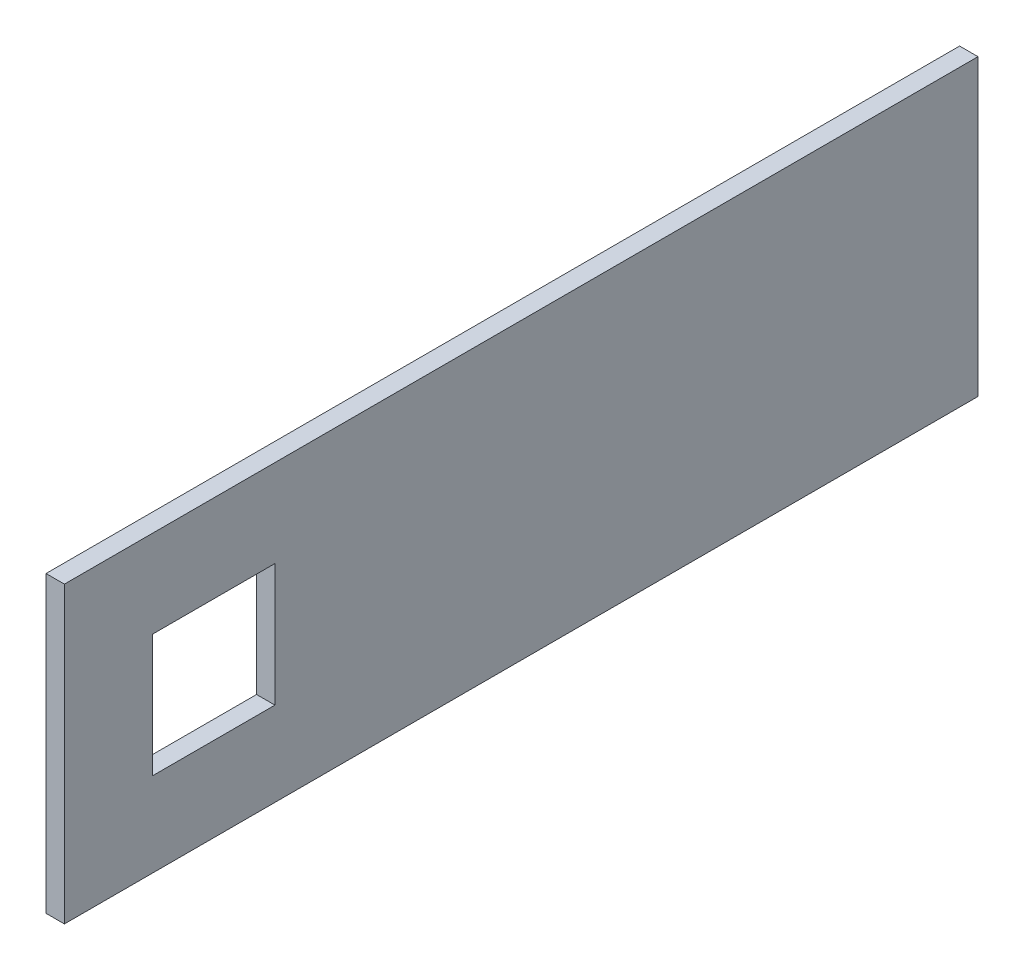
SolidWorks part; units mm, degrees
ref_plane "Front Plane" through (0, 0, 0) normal (0, 0, 1) x (1, 0, 0)
ref_plane "Top Plane" through (0, 0, 0) normal (0, 1, 0) x (1, 0, 0)
ref_plane "Right Plane" through (0, 0, 0) normal (1, 0, 0) x (0, 0, -1)
sketch "Sketch1" plane through (0, 0, 0) normal (1, 0, 0) x (0, 0, -1)
  line L1 (-74.5, 24) -> (74.5, 24)
  line L2 (-74.5, 24) -> (-74.5, -24)
  line L3 (-74.5, -24) -> (74.5, -24)
  line L4 (74.5, 24) -> (74.5, -24)
  line L5 (-74.5, 24) -> (74.5, -24) construction
  line L6 (-74.5, -24) -> (74.5, 24) construction
  line L7 (-60.1601, 9.7414) -> (-40.1601, 9.7414)
  line L8 (-60.1601, 9.7414) -> (-60.1601, -10.2586)
  line L9 (-60.1601, -10.2586) -> (-40.1601, -10.2586)
  line L10 (-40.1601, 9.7414) -> (-40.1601, -10.2586)
  line L11 (-60.1601, 9.7414) -> (-40.1601, -10.2586) construction
  line L12 (-60.1601, -10.2586) -> (-40.1601, 9.7414) construction
  point P0 (0, 0)
  point P6 (-50.1601, -0.2586)
  point P11 (0, 0)
  dimension "D1" = 149
  dimension "D2" = 48
  dimension "D3" = 20
  dimension "D4" = 20
extrude "Boss-Extrude2" add sketch "Sketch1" along normal blind 3
